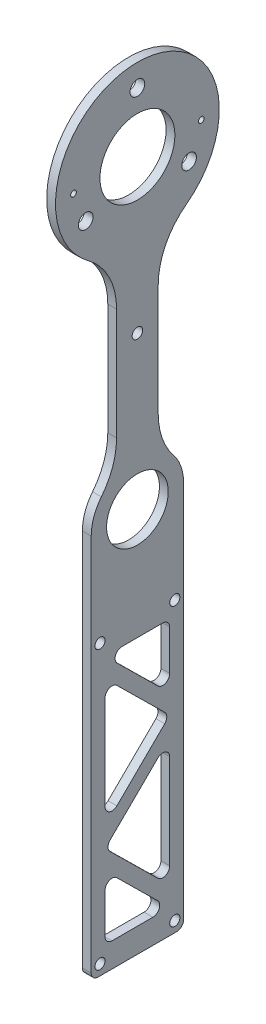
SolidWorks part; units mm, degrees
material "6061 Alloy"
ref_plane "Front Plane" through (0, 0, 0) normal (0, 0, 1) x (1, 0, 0)
ref_plane "Top Plane" through (0, 0, 0) normal (0, 1, 0) x (1, 0, 0)
ref_plane "Right Plane" through (0, 0, 0) normal (1, 0, 0) x (0, 0, -1)
sketch "Sketch1" plane through (0, 0, 0) normal (1, 0, 0) x (0, 0, -1)
  line L0 (-13.4747, 0) -> (13.4747, 0) construction
  line L1 (0, 0) -> (0, 23.8875) construction
  line L2 (-13.4747, 0) -> (-3.9926, 24.6295) construction
  line L3 (0, 35) -> (5.9803, 19.4664) construction
  line L4 (13.4747, 0) -> (-13.4747, 0) construction
  line L5 (20.7574, -5) -> (-20.7574, -5)
  line L6 (-20.7574, -5) -> (-10.1693, 22.5021)
  line L7 (1.1006, 46.0579) -> (10.3702, 21.9802) construction
  line L8 (0, 35) -> (0, 46.1125) construction
  line L9 (0, 35) -> (0, 46.1125) construction
  line L12 (-7.5, 20.1405) -> (-7.5, 43.1999) construction
  line L13 (7.5, 49.8595) -> (7.5, 43.1999) construction
  line L14 (-16.645, 35) -> (-16.645, 5.6818)
  line L15 (16.645, 35) -> (16.645, 5.6818)
  line L16 (-13.4747, 0) -> (13.4747, 0) construction
  line L17 (-13.4747, 0) -> (-13.4747, -100) construction
  line L18 (13.4747, 0) -> (13.4747, -100) construction
  line L19 (-13.4747, -100) -> (13.4747, -100) construction
  line L20 (-20.7574, -5) -> (20.7574, -5)
  line L21 (-20.7574, -5) -> (-20.7574, -103.81)
  line L22 (20.7574, -5) -> (20.7574, -103.81)
  line L23 (-20.7574, -103.81) -> (20.7574, -103.81)
  line L24 (-10.1693, 22.5021) -> (-8.2317, 27.535) construction
  line L25 (-16.645, 5.6818) -> (-10.3702, 21.9802) construction
  line L26 (-20.7574, -5) -> (0, 48.9165) construction
  line L27 (8.2317, 27.535) -> (10.1693, 22.5021) construction
  line L28 (10.1693, 22.5021) -> (20.7574, -5)
  line L29 (0, 48.9165) -> (20.7574, -5) construction
  line L30 (-7.5, 43.1999) -> (-7.5, 49.2605) construction
  line L31 (-7.5, 49.2605) -> (-7.5, 144.656)
  line L32 (7.5, 43.1999) -> (7.5, 49.2605) construction
  line L33 (7.5, 49.2605) -> (7.5, 145.344)
  line L34 (-1.1006, 46.0579) -> (0, 48.9165) construction
  line L35 (0, 46.1125) -> (0, 48.9165) construction
  line L36 (0, 48.9165) -> (0, 145) construction
  line L37 (0, 46.1125) -> (0, 48.9165) construction
  line L38 (0, 48.9165) -> (0, 145) construction
  line L39 (0, 48.9165) -> (1.1006, 46.0579) construction
  line L40 (-8.2317, 27.535) -> (-16.645, 5.6818) construction
  line L41 (-3.9926, 24.6295) -> (-5.9803, 19.4664) construction
  line L42 (-5.9803, 19.4664) -> (0, 35) construction
  line L43 (-13.4747, 0) -> (0, 35) construction
  line L44 (0, 23.8875) -> (0, 18.355) construction
  line L45 (0, 18.355) -> (0, 35) construction
  line L46 (5.9803, 19.4664) -> (3.9926, 24.6295) construction
  line L47 (3.9926, 24.6295) -> (13.4747, 0) construction
  line L48 (0, 35) -> (13.4747, 0) construction
  line L49 (16.645, 5.6818) -> (8.2317, 27.535) construction
  line L50 (10.3702, 21.9802) -> (16.645, 5.6818) construction
  line L51 (-10.3702, 21.9802) -> (-1.1006, 46.0579) construction
  line L52 (-7.5, 96.9583) -> (7.5, 96.9583) construction
  circle A0 centre (-13.4747, 0) radius 1.8288
  circle A1 centre (0, 35) radius 11.1125
  circle A2 centre (13.4747, 0) radius 1.8288
  circle A3 centre (0, 145) radius 3 construction
  arc A6 (-7.5, 20.1405) -> (-10.3702, 21.9802) centre (0, 35) ccw
  arc A7 (7.5, 145.344) -> (-7.5, 144.656) centre (0, 145) ccw
  circle A8 centre (-13.4747, -100) radius 1.8288
  circle A9 centre (13.4747, -100) radius 1.8288
  circle A10 centre (0, 145) radius 21.5 construction
  circle A11 centre (0, 166.5) radius 2.65
  circle A12 centre (-18.6195, 134.25) radius 2.65
  circle A13 centre (18.6195, 134.25) radius 2.65
  arc A14 (0, 166.5) -> (-18.6195, 134.25) centre (0, 145) ccw construction
  arc A15 (0, 166.5) -> (18.6195, 134.25) centre (0, 145) cw construction
  arc A16 (-18.6195, 134.25) -> (18.6195, 134.25) centre (0, 145) ccw construction
  circle A17 centre (0, 145) radius 13.5
  circle A18 centre (0, 145) radius 29.5
  arc A19 (10.1693, 22.5021) -> (7.5, 49.2605) centre (0, 35) ccw
  arc A20 (-10.1693, 22.5021) -> (-5.789, 19.9634) centre (0, 35) ccw construction
  circle A21 centre (0, 35) radius 16.1125 construction
  arc A22 (-5.789, 19.9634) -> (0, 18.8875) centre (0, 35) ccw construction
  arc A23 (0, 18.8875) -> (5.789, 19.9634) centre (0, 35) ccw construction
  arc A24 (5.789, 19.9634) -> (10.1693, 22.5021) centre (0, 35) ccw construction
  arc A25 (0, 51.1125) -> (-7.5, 49.2605) centre (0, 35) ccw construction
  arc A26 (-7.5, 49.2605) -> (-10.1693, 22.5021) centre (0, 35) ccw
  arc A27 (7.5, 49.2605) -> (0, 51.1125) centre (0, 35) ccw construction
  arc A28 (5.9803, 19.4664) -> (10.3702, 21.9802) centre (0, 35) ccw construction
  arc A29 (10.3702, 21.9802) -> (7.5, 49.8595) centre (0, 35) ccw construction
  arc A30 (-5.9803, 19.4664) -> (0, 18.355) centre (0, 35) ccw construction
  arc A31 (0, 18.355) -> (5.9803, 19.4664) centre (0, 35) ccw construction
  arc A32 (-10.3702, 21.9802) -> (-5.9803, 19.4664) centre (0, 35) ccw construction
  point P4 (0, 0)
  point P14 (0, 90)
  point P34 (0, 145)
  point P67 (0, 96.9583)
  dimension "D3" = 3.6576
  dimension "D4" = 22.225
  dimension "D7" = 6
  dimension "D11" = 43
  dimension "D12" = 5.3
  dimension "D13" = 27
  dimension "D14" = 59
  dimension "D16" = 16.645
  dimension "D1" = 26.9494
  dimension "D5" = 110
  dimension "D6" = 15
  dimension "D8" = 100
  dimension "D9" = 3.81
  dimension "D10" = 35
  dimension "D15" = 5
  dimension "D2" = 5
extrude "Boss-Extrude1" add sketch "Sketch1" along normal blind 3.175
sketch "Sketch2" plane through (3.175, 0, 0) normal (1, 0, 0) x (0, 0, -1)
  line L0 (-11.645, -5) -> (11.645, -5) construction
  line L1 (-11.645, -95) -> (11.645, -95) construction
  line L2 (11.645, -95) -> (11.645, -5) construction
  line L3 (-11.645, -95) -> (-11.645, -5) construction
  line L6 (11.645, -38.5118) -> (-11.645, -61.4882) construction
  line L7 (11.645, -5) -> (-11.645, -5)
  line L8 (-11.645, -5) -> (11.645, -27.9764)
  line L9 (11.645, -27.9764) -> (11.645, -5)
  line L10 (-11.645, -12.0236) -> (11.645, -35)
  line L11 (11.645, -35) -> (-11.645, -57.9764)
  line L12 (-11.645, -57.9764) -> (-11.645, -35)
  line L13 (-11.645, -35) -> (-11.645, -12.0236)
  line L14 (-11.645, -72.0236) -> (-11.645, -95)
  line L15 (-11.645, -95) -> (11.645, -95)
  line L16 (11.645, -95) -> (-11.645, -72.0236)
  line L17 (11.645, -42.0236) -> (11.645, -65)
  line L18 (11.645, -65) -> (11.645, -87.9764)
  line L19 (11.645, -87.9764) -> (-11.645, -65)
  line L20 (-11.645, -65) -> (11.645, -42.0236)
  line L21 (16.645, -1056.0877) -> (16.645, 48943.9123) construction
  line L22 (-16.645, -1060.2922) -> (-16.645, 48939.7078) construction
  line L23 (16.645, 23.8875) -> (-16.645, 23.8875) construction
  line L24 (-20.7574, -103.81) -> (-16.645, -103.81)
  line L25 (-20.7574, -103.81) -> (-20.7574, 23.8875)
  line L26 (-16.645, -103.81) -> (-16.645, 23.8875)
  line L27 (-20.7574, 23.8875) -> (-16.645, 23.8875)
  line L28 (-20.7574, -103.81) -> (20.7574, -103.81) construction
  line L29 (20.7574, -103.81) -> (16.645, -103.81)
  line L30 (20.7574, -103.81) -> (20.7574, 23.8875)
  line L31 (16.645, -103.81) -> (16.645, 23.8875)
  line L32 (20.7574, 23.8875) -> (16.645, 23.8875)
  circle A0 centre (13.4747, 0) radius 1.8288 construction
  circle A1 centre (13.4747, -100) radius 1.8288 construction
  circle A2 centre (0, 35) radius 11.1125 construction
  point P6 (11.645, -50)
  point P10 (0, 23.8875)
  point P21 (0, -50)
  dimension "D1" = 33.29
  dimension "D2" = 5
  dimension "D3" = 5
  dimension "D4" = 5
  dimension "D5" = 5
  dimension "D6" = 2.5
  dimension "D8" = 5
  dimension "D7" = 2
extrude "Cut-Extrude1" cut sketch "Sketch2" against normal up to next
fillet "Fillet3" radius 2.5 14 edges at (1.5875, -57.9764, 11.645) (1.5875, -35, -11.645) (1.5875, -95, -11.645) (1.5875, -72.0236, 11.645) (1.5875, -95, 11.645) (1.5875, -27.9764, -11.645) (1.5875, -5, -11.645) (1.5875, -12.0236, 11.645) (1.5875, -5, 11.645) (1.5875, -87.9764, -11.645) (1.5875, -42.0236, -11.645) (1.5875, -65, 11.645) (1.5875, -103.81, -16.645) (1.5875, -103.81, 16.645)
fillet "Fillet4" radius 25 4 edges at (1.5875, 116.4693, 7.5) (1.5875, 116.4693, -7.5) (1.5875, 49.8595, -7.5) (1.5875, 49.8595, 7.5)
hole_wizard "M2.5x0.45 Tapped Hole1" positions "Sketch3" profile "Sketch4" tap size "M2.5x0.45" standard "ANSI Metric" end condition up to next
sketch "Sketch3" plane through (3.175, 0, 0) normal (1, 0, 0) x (0, 0, -1)
  line L0 (0, 166.5) -> (0, 145) construction
  line L2 (0, 145) -> (50000, 145) construction
  circle A0 centre (0, 145) radius 23.015 construction
  point P15 (-23.015, 145)
  point P17 (23.015, 145)
  dimension "D1" = 46.03
sketch "Sketch4" plane through (3.175, 145, -23.015) normal (0, 1, 0) x (0, 0, -1)
  line L0 (0, 0) -> (0, 3.175)
  line L1 (0, 3.175) -> (1.025, 3.175)
  line L2 (1.025, 3.175) -> (1.025, 0)
  line L5 (1.025, 0) -> (0, 0)
  line L11 (0, -6.35) -> (0, 107.95) construction
  dimension "Thru Tap Drill Dia." = 2.05
  dimension "Thru Tap Drill Depth" = 3.175
cosmetic thread "Hole Thread1" parameters "D2"=2.5
cosmetic thread "Hole Thread2" parameters "D2"=2.5
hole_wizard "#6 Clearance Hole1" positions "Sketch5" profile "Sketch6" hole size "#6" standard "ANSI Inch" end condition through all
sketch "Sketch5" plane through (3.175, 0, 0) normal (1, 0, 0) x (0, 0, -1)
  circle A0 centre (0, 35) radius 11.1125 construction
  point P0 (0, 90)
  dimension "D1" = 55
sketch "Sketch6" plane through (3.175, 90, 0) normal (0, 1, 0) x (0, 0, -1)
  line L0 (0, 0) -> (0, 3.175)
  line L1 (0, 3.175) -> (1.8986, 3.175)
  line L2 (1.8986, 3.175) -> (1.8986, 0)
  line L5 (1.8986, 0) -> (0, 0)
  line L11 (0, -6.35) -> (0, 107.95) construction
  dimension "Thru Hole Dia." = 3.7973
  dimension "Thru Hole Depth" = 3.175
